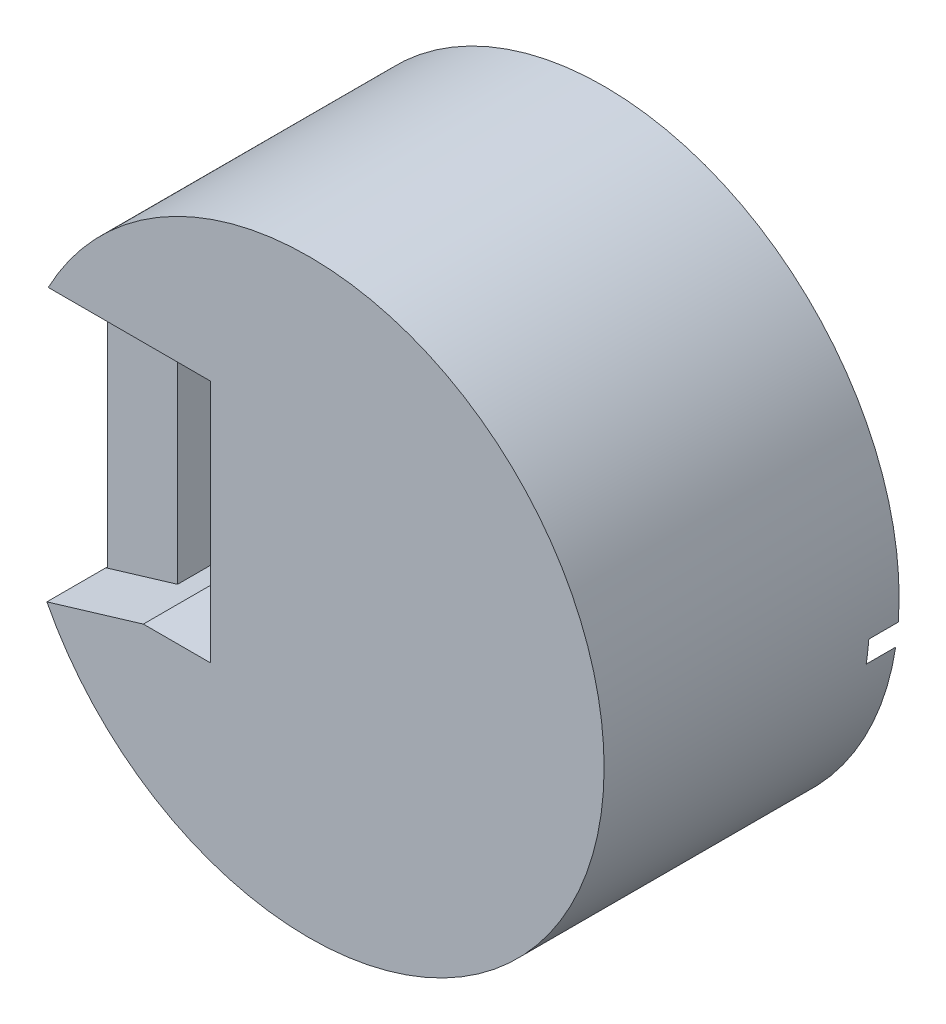
SolidWorks part; units mm, degrees
ref_plane "前基準面" through (0, 0, 0) normal (0, 0, 1) x (1, 0, 0)
ref_plane "上基準面" through (0, 0, 0) normal (0, 1, 0) x (1, 0, 0)
ref_plane "右基準面" through (0, 0, 0) normal (1, 0, 0) x (0, 0, -1)
sketch "草圖1" plane through (0, 0, 0) normal (0, 0, 1) x (1, 0, 0)
  circle A0 centre (0, 0) radius 10
extrude "填料-伸長1" add sketch "草圖1" along normal blind 10 contours A0
sketch "草圖2" plane through (0, 0, 10) normal (0, 0, 1) x (1, 0, 0)
  line L1 (-5.6191, 4.6712) -> (-3.335, 4.6712)
  line L2 (-5.6191, 4.6712) -> (-5.6191, -3.6)
  line L3 (-5.6191, -3.6) -> (-3.335, -3.6)
  line L4 (-3.335, 4.6712) -> (-3.335, -3.6)
extrude "除料-伸長1" cut sketch "草圖2" against normal blind 10 contours L1 L4 L3 L2
sketch "草圖3" plane through (0, 0, 10) normal (0, 0, 1) x (1, 0, 0)
  line L0 (-5.6191, 4.6712) -> (-8.8419, 4.6712)
  line L1 (-8.8888, -4.5814) -> (-5.6191, -3.6)
  line L2 (-5.6191, -3.6) -> (-5.6191, 4.6712)
  circle A0 centre (0, 0) radius 10 construction
  arc A1 (-8.8419, 4.6712) -> (-8.8888, -4.5814) centre (-2.3388, 0.0118) ccw
extrude "除料-伸長2" cut sketch "草圖3" against normal blind 2 contours L1 L2 L0 A1
sketch "草圖4" plane through (0, 0, 0) normal (0, 0, -1) x (-1, 0, 0)
  line L0 (5.6191, 4.6712) -> (8.8419, 4.6712)
  line L1 (8.8617, -4.6337) -> (5.6191, -4.6337)
  line L2 (5.6191, -4.6337) -> (5.6191, 4.6712)
  circle A0 centre (0, 0) radius 10 construction
  arc A1 (8.8419, 4.6712) -> (8.8617, -4.6337) centre (2.3438, 0.005) cw
extrude "除料-伸長3" cut sketch "草圖4" against normal blind 2
ref_plane "平面1" through (-12.335, 0, 0) normal (-1, 0, 0) x (0, 0, 1)
sketch "草圖7" plane through (-12.335, 0, 0) normal (-1, 0, 0) x (0, 0, 1)
  line L0 (2, 4.6712) -> (8, 4.6712)
  line L1 (8, 4.6712) -> (8, -4.5814)
  line L2 (8, -4.5814) -> (2, -4.6337)
  line L3 (2, -4.6337) -> (2, 4.6712)
extrude "除料-伸長4" cut sketch "草圖7" against normal blind 3.5
sketch "草圖9" plane through (0, 0, 8) normal (0, 0, 1) x (1, 0, 0)
  line L0 (-5.6191, 4.6146) -> (-5.6191, -3.6)
  line L1 (-5.6191, -3.6) -> (-5.6191, 4.6712) construction
  line L2 (-8.835, -4.5652) -> (-5.6191, -3.6) construction
  line L3 (-5.6191, -3.6) -> (-6.4583, -3.8519)
  line L4 (-6.4583, -3.8519) -> (-6.4583, 4.6146)
  line L5 (-6.4583, 4.6146) -> (-5.6191, 4.6146)
extrude "除料-伸長5" cut sketch "草圖9" against normal blind 8
sketch "草圖10" plane through (1.1472, 0, 0) normal (0, 0, -1) x (-1, 0, 0)
  circle A0 centre (-4.7794, 2.8446) radius 2
  point P2 (0, 0)
  point P3 (-5.4999, 3.6188)
  point P4 (-4.7794, 2.8446)
extrude "除料-伸長6" cut sketch "草圖10" against normal blind 1
sketch "草圖11" plane through (3.9506, 2.0622, 0) normal (0, 0, -1) x (-1, 0, 0)
  arc A0 (-6.1346, -3.2795) -> (2.4862, -6.0868) centre (-0.16, 0.4275) ccw
  arc A1 (-6.1346, -3.2795) -> (-5.5552, -2.9199) centre (-5.8449, -3.0997) cw
  arc A2 (-5.5552, -2.9199) -> (2.2452, -5.3097) centre (-0.4601, -0.2146) ccw
  arc A3 (2.2452, -5.3097) -> (2.4862, -6.0868) centre (2.3657, -5.6983) cw
extrude "除料-伸長7" cut sketch "草圖11" against normal blind 1
sketch "草圖15" plane through (0.572, 0, 1) normal (0, 0, -1) x (-1, 0, 0)
  circle A0 centre (-5.9266, 2.8446) radius 0.5984
extrude "填料-伸長5" add sketch "草圖15" along normal blind 1
